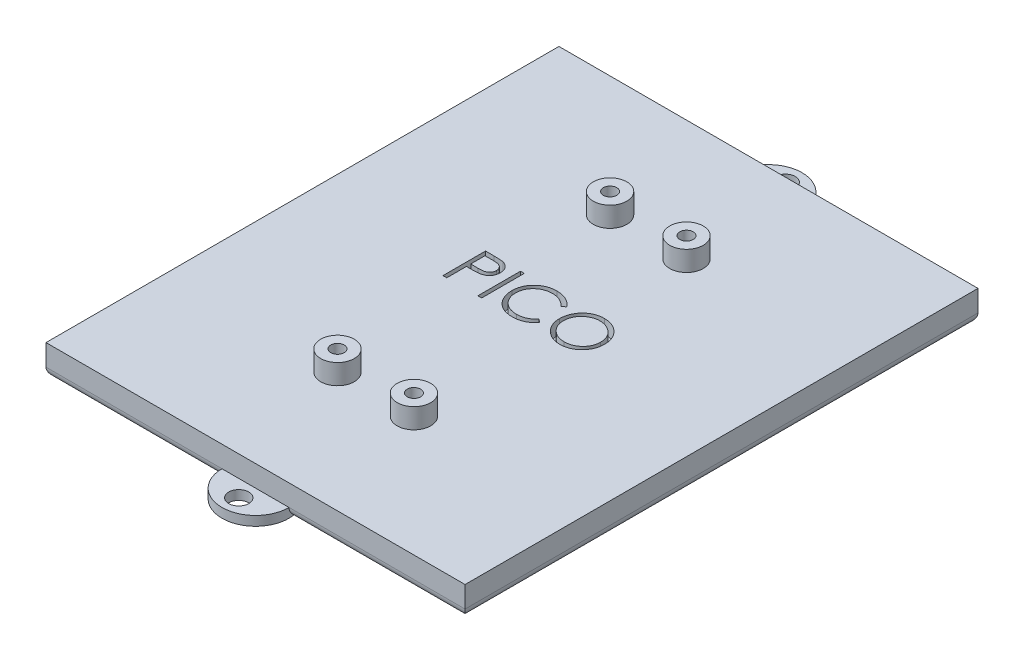
SolidWorks part; units mm, degrees
ref_plane "Front Plane" through (0, 0, 0) normal (0, 0, 1) x (1, 0, 0)
ref_plane "Top Plane" through (0, 0, 0) normal (0, 1, 0) x (1, 0, 0)
ref_plane "Right Plane" through (0, 0, 0) normal (1, 0, 0) x (0, 0, -1)
sketch "Sketch1" plane through (0, 0, 0) normal (0, 1, 0) x (1, 0, 0)
  line L0 (-31.25, 38.25) -> (31.25, 38.25)
  line L5 (-31.25, 38.25) -> (-31.25, -38.25)
  line L6 (-31.25, -38.25) -> (31.25, -38.25)
  line L7 (31.25, 38.25) -> (31.25, -38.25)
  point P11 (-31.25, 0)
  point P12 (0, -38.25)
  dimension "D3" = 76.5
  dimension "D4" = 62.5
extrude "Boss-Extrude1" add sketch "Sketch1" along normal blind 4.575
sketch "Sketch4" plane through (0, 0, 0) normal (0, 1, 0) x (1, 0, 0)
  line L0 (-5, -38.25) -> (5, -38.25)
  line L2 (-31.25, -38.25) -> (31.25, -38.25) construction
  line L4 (0, -38.25) -> (0, -43.25) construction
  arc A0 (-5, -38.25) -> (5, -38.25) centre (0, -38.25) ccw
  circle A2 centre (0, -40.75) radius 1.5
  dimension "D2" = 3
  dimension "D3" = 5
extrude "Boss-Extrude3" add sketch "Sketch4" along normal blind 1.4
mirror "Mirror1" about plane through (0, 0, 0) normal (0, 0, 1) of "Boss-Extrude3"
fillet "Fillet1" radius 1.4 6 edges at (-18.125, 0, 38.25) (18.125, 0, 38.25) (31.25, 0, 0) (18.125, 0, -38.25) (-18.125, 0, -38.25) (-31.25, 0, 0)
sketch "Sketch2" plane through (0, 4.575, 0) normal (0, 1, 0) x (1, 0, 0)
  line L1 (-5.7, 20.3255) -> (5.7, 20.3255) construction
  line L2 (5.7, 20.3255) -> (5.7, -20.3255) construction
  line L3 (5.7, -20.3255) -> (-5.7, -20.3255) construction
  line L4 (-5.7, -20.3255) -> (-5.7, 20.3255) construction
  circle A8 centre (-5.7, 20.3255) radius 1
  circle A9 centre (5.7, 20.3255) radius 1
  circle A10 centre (-5.7, -20.3255) radius 1
  circle A11 centre (5.7, -20.3255) radius 1
  circle A12 centre (-5.7, -20.3255) radius 2.5
  circle A13 centre (5.7, -20.3255) radius 2.5
  circle A14 centre (5.7, 20.3255) radius 2.5
  circle A15 centre (-5.7, 20.3255) radius 2.5
  point P8 (5.7, 0)
  point P9 (0, 20.3255)
  dimension "D1" = 2
  dimension "D4" = 1.5
  dimension "D2" = 40.651
  dimension "D3" = 11.4
extrude "Screw_Holes" add sketch "Sketch2" along normal blind 3
sketch "Sketch3" plane through (0, 4.575, 0) normal (0, 1, 0) x (1, 0, 0)
  circle A0 centre (5.7, -20.3255) radius 1
  circle A1 centre (-5.7, -20.3255) radius 1
  circle A2 centre (-5.7, 20.3255) radius 1
  circle A3 centre (5.7, 20.3255) radius 1
  circle A6 centre (-5.7, -20.3255) radius 1 construction
  point P12 (0, 0)
  point P13 (-5.3705, -24.3431)
  point P14 (-7.6205, -20.3255)
  point P16 (0, 0)
  point P17 (0, 0)
  point P18 (0, 0)
  point P21 (7.6205, -20.3255)
  point P23 (14.0733, 19.5755)
  point P24 (7.6205, 20.3255)
  point P26 (-7.6205, 20.3255)
extrude "Cut-Extrude1" cut sketch "Sketch3" against normal offset from surface (3.575 mm away) 1
sketch "Sketch5" plane through (0, 4.575, 0) normal (0, 1, 0) x (1, 0, 0)
  line L0 (-15, 0) -> (15, 0) construction
  text T0 "PICO\r\n" font "Century Gothic" height in points 24
  point P4 (14.3725, 0)
  point P5 (10.1548, 0)
  point P6 (0, 0)
  point P7 (0, 0)
  dimension "D1" = 30
extrude "Letters" cut sketch "Sketch5" against normal blind 2
